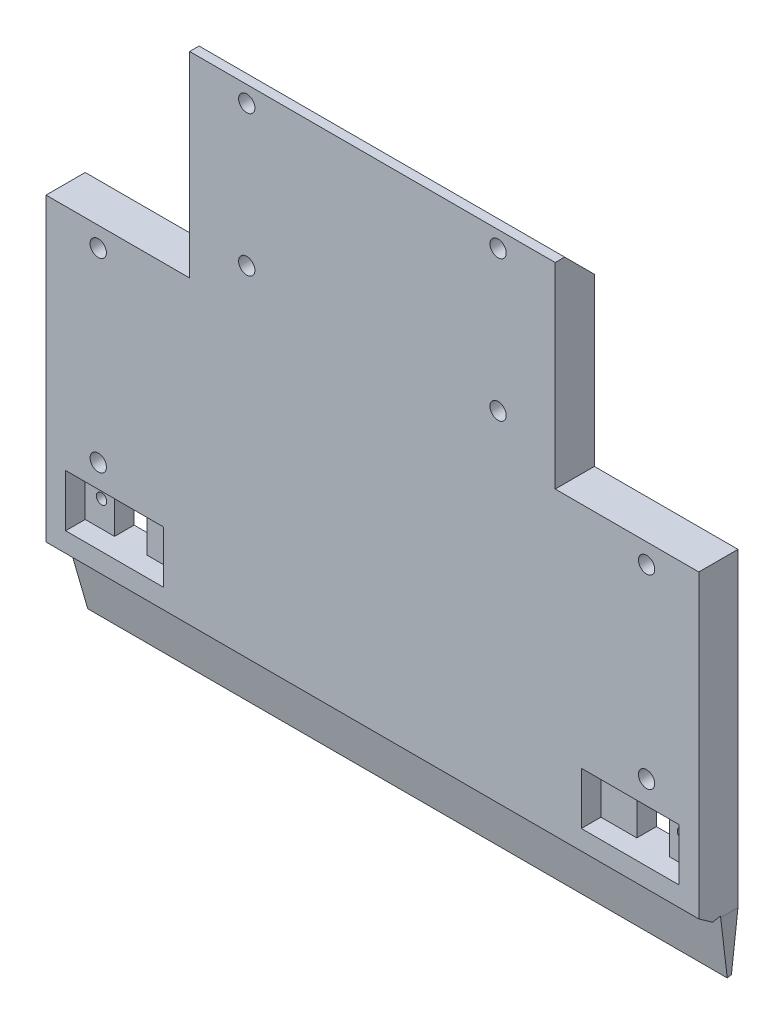
SolidWorks part; units mm, degrees
material "7075-T6, Chapa (SS)"
ref_plane "Plano frontal" through (0, 0, 0) normal (0, 0, 1) x (1, 0, 0)
ref_plane "Plano superior" through (0, 0, 0) normal (0, 1, 0) x (1, 0, 0)
ref_plane "Plano direito" through (0, 0, 0) normal (1, 0, 0) x (0, 0, -1)
sketch "Esboço1" plane through (0, 0, 0) normal (0, 0, 1) x (1, 0, 0)
  line L0 (0, 62) -> (22, 62)
  line L2 (0, 62) -> (0, 0)
  line L3 (0, 0) -> (100, 0)
  line L4 (100, 62) -> (100, 0)
  line L7 (78, 96) -> (22, 96)
  line L17 (22, 62) -> (22, 96)
  line L18 (78, 96) -> (78, 62)
  line L19 (78, 62) -> (100, 62)
  dimension "D1" = 100
  dimension "D2" = 96
  dimension "D3" = 34
  dimension "D4" = 22
  dimension "D5" = 22
  dimension "D6" = 34
  dimension "D7" = 0
  dimension "D8" = 0
extrude "Ressalto-extrusão1" add sketch "Esboço1" along normal blind 6
sketch "Esboço2" plane through (0, 0, 0) normal (-1, 0, 0) x (0, 0, 1)
  line L0 (0, 0) -> (2.7029, 12.7159)
  line L1 (4.346, 12.7159) -> (6, 12.7159)
  line L2 (6, 62) -> (6, 0) construction
  line L3 (6, 12.7159) -> (6, 0)
  line L4 (6, 0) -> (0, 0)
  line L5 (0, 62) -> (0, 0) construction
  line L6 (2.7029, 12.7159) -> (4.2749, 12.3818)
  line L7 (4.2749, 12.3818) -> (4.346, 12.7159)
  dimension "D1" = 12
  dimension "D2" = 13
  dimension "D3" = 90
extrude "Corte-extrusão1" cut sketch "Esboço2" against normal blind 100
sketch "Esboço3" plane through (78, 0, 0) normal (1, 0, 0) x (0, 0, -1)
  line L0 (-6, 91.5) -> (0, 85.5)
  line L1 (-6, 62) -> (-6, 96) construction
  line L2 (0, 62) -> (0, 96) construction
  line L3 (0, 85.5) -> (0, 96)
  line L4 (0, 96) -> (-6, 96)
  line L5 (-6, 96) -> (0, 96) construction
  line L6 (-6, 96) -> (-6, 91.5)
  dimension "D1" = 4.5
  dimension "D2" = 45
extrude "Corte-extrusão2" cut sketch "Esboço3" against normal blind 100
sketch "Esboço4" plane through (100, 0, 0) normal (1, 0, 0) x (0, 0, -1)
  line L0 (-4.2749, 12.3818) -> (-2.7029, 12.7159) construction
  line L1 (-6, 12.7159) -> (-6, 62) construction
  line L2 (-3.8766, 12.4664) -> (-6, 11.8318)
  line L3 (-6, 11.8318) -> (-6, 13.9664)
  line L4 (-6, 13.9664) -> (-3.8766, 12.4664)
  dimension "D1" = 1.2
  dimension "D2" = 1.5
extrude "Corte-extrusão3" cut sketch "Esboço4" against normal blind 100
fillet "Filete1" radius 0.1 1 edges at (50, 0, 0)
sketch "Esboço5" plane through (0, 0, 6) normal (0, 0, 1) x (1, 0, 0)
  line L0 (0, 12.4664) -> (1.3138, 0.1687)
  line L1 (0, 12.4664) -> (100, 12.4664) construction
  line L2 (0, 12.4664) -> (0, 13.9664) construction
  line L3 (1.3138, 0.1687) -> (0, 0.8514)
  line L4 (0, 0.8514) -> (100, 0.8514) construction
  line L5 (0, 0.8514) -> (0, 12.4664)
  line L6 (100, 12.4664) -> (98.6862, 0.1687)
  line L7 (100, 12.7159) -> (100, 0.9306) construction
  line L8 (98.6862, 0.1687) -> (100, 0.8514)
  line L9 (100, 0.8514) -> (100, 12.4664)
extrude "Corte-extrusão4" cut sketch "Esboço5" against normal blind 100
hole_wizard "Broca de rosquear para tarraxa de M31" positions "Esboço7" profile "Esboço8" hole size "M3" standard "ISO" end condition through all
sketch "Esboço7" plane through (0, 0, 6) normal (0, 0, 1) x (1, 0, 0)
  point P0 (92, 56.9664)
  point P2 (92, 28.5209)
  point P4 (8, 56.9664)
  point P6 (8, 28.5209)
sketch "Esboço8" plane through (92, 56.9664, 6) normal (1, 0, 0) x (0, -1, 0)
  line L0 (0, 0) -> (0, 6)
  line L1 (0, 6) -> (1.25, 6)
  line L2 (1.25, 6) -> (1.25, 0)
  line L5 (1.25, 0) -> (0, 0)
  line L11 (0, -6.35) -> (0, 107.95) construction
  dimension "Thru Hole Dia." = 2.5
  dimension "Thru Hole Depth" = 6
sketch "Esboço9" plane through (0, 0, 6) normal (0, 0, 1) x (1, 0, 0)
  line L0 (0, 62) -> (0, 13.9664) construction
  line L1 (3, 16.9664) -> (18, 16.9664)
  line L2 (3, 16.9664) -> (3, 24.9664)
  line L3 (3, 24.9664) -> (18, 24.9664)
  line L4 (18, 16.9664) -> (18, 24.9664)
  line L5 (97, 16.9664) -> (82, 16.9664)
  line L6 (97, 16.9664) -> (97, 24.9664)
  line L7 (97, 24.9664) -> (82, 24.9664)
  line L8 (82, 16.9664) -> (82, 24.9664)
  line L9 (100, 13.9664) -> (100, 62) construction
  line L10 (0, 13.9664) -> (100, 13.9664) construction
  dimension "D1" = 8
  dimension "D2" = 15
  dimension "D3" = 3
  dimension "D4" = 8
  dimension "D5" = 3
  dimension "D6" = 15
  dimension "D7" = 3
  dimension "D8" = 3
extrude "Corte-extrusão5" cut sketch "Esboço9" against normal blind 3
sketch "Esboço10" plane through (0, 0, 0) normal (0, 0, -1) x (-1, 0, 0)
  line L0 (-100, 12.4664) -> (-100, 62) construction
  line L1 (-87.5, 16.9664) -> (-92.5, 16.9664)
  line L2 (-87.5, 16.9664) -> (-87.5, 24.9664)
  line L3 (-87.5, 24.9664) -> (-92.5, 24.9664)
  line L4 (-92.5, 16.9664) -> (-92.5, 24.9664)
  line L5 (-50, 93.4018) -> (-50, -39.1507) construction
  line L6 (-12.5, 16.9664) -> (-7.5, 16.9664)
  line L7 (-7.5, 16.9664) -> (-7.5, 24.9664)
  line L8 (-12.5, 24.9664) -> (-7.5, 24.9664)
  line L9 (-12.5, 16.9664) -> (-12.5, 24.9664)
  line L10 (-3, 24.9664) -> (-3, 16.9664) construction
  dimension "D1" = 5
  dimension "D2" = 8
  dimension "D3" = 7.5
  dimension "D4" = 4.5
extrude "Corte-extrusão6" cut sketch "Esboço10" against normal blind 3
hole_wizard "Broca de rosquear para tarraxa de M21" positions "Esboço11" profile "Esboço12" hole size "M2" standard "ISO" end condition through all
sketch "Esboço11" plane through (0, 0, 3) normal (0, 0, 1) x (1, 0, 0)
  line L1 (82, 16.9664) -> (97, 16.9664) construction
  line L2 (89.5, 16.9664) -> (89.5, 24.9664) construction
  line L3 (97, 24.9664) -> (82, 24.9664) construction
  line L4 (10.5, 16.9664) -> (10.5, 24.9664) construction
  line L5 (3, 16.9664) -> (18, 16.9664) construction
  line L6 (18, 24.9664) -> (3, 24.9664) construction
  circle A0 centre (84.5, 20.9664) radius 0.8262
  circle A1 centre (94.5, 20.9664) radius 0.8262
  circle A2 centre (15.5, 20.9664) radius 0.819
  circle A3 centre (5.5, 20.9664) radius 0.819
  point P18 (94.5, 20.9664)
  point P35 (5.5, 20.9664)
sketch "Esboço12" plane through (5.5, 20.9664, 3) normal (1, 0, 0) x (0, -1, 0)
  line L0 (0, 0) -> (0, 3)
  line L1 (0, 3) -> (0.8, 3)
  line L2 (0.8, 3) -> (0.8, 0)
  line L5 (0.8, 0) -> (0, 0)
  line L11 (0, -6.35) -> (0, 107.95) construction
  dimension "Thru Hole Dia." = 1.6
  dimension "Thru Hole Depth" = 3
hole_wizard "Broca de rosquear para tarraxa de M32" positions "Esboço13" profile "Esboço14" hole size "M3" standard "ISO" end condition through all
sketch "Esboço13" plane through (0, 0, 0) normal (0, 0, -1) x (-1, 0, 0)
  point P0 (-30.75, 66)
  point P4 (-69.25, 66)
  point P6 (-69.25, 87.5515)
  point P10 (-30.75, 87.5515)
sketch "Esboço14" plane through (30.75, 66, 0) normal (1, 0, 0) x (0, 1, 0)
  line L0 (0, 0) -> (0, 6)
  line L1 (0, 6) -> (1.25, 6)
  line L2 (1.25, 6) -> (1.25, 0)
  line L5 (1.25, 0) -> (0, 0)
  line L11 (0, -6.35) -> (0, 107.95) construction
  dimension "Thru Hole Dia." = 2.5
  dimension "Thru Hole Depth" = 6
sketch "Esboço15" plane through (0, 0, 6) normal (0, 0, 1) x (1, 0, 0)
  line L0 (22, 91.5) -> (22, 62) construction
  line L1 (22, 90.0515) -> (78.2659, 90.0515)
  line L2 (22, 90.0515) -> (22, 95.4615)
  line L3 (22, 95.4615) -> (78.2659, 95.4615)
  line L4 (78.2659, 90.0515) -> (78.2659, 95.4615)
extrude "Corte-extrusão7" cut sketch "Esboço15" against normal blind 5
sketch "Esboço16" plane through (0, 0, 0) normal (0, 0, -1) x (-1, 0, 0)
  line L0 (0, 62) -> (0, 12.4664) construction
  line L1 (0, 62) -> (-22, 62)
  line L2 (0, 62) -> (0, 60)
  line L3 (0, 60) -> (-22, 60)
  line L4 (-22, 62) -> (-22, 60)
  line L5 (-22, 62) -> (0, 62) construction
  line L6 (-100, 62) -> (-78, 62) construction
  line L7 (-78, 62) -> (-100, 62)
  line L8 (-78, 62) -> (-78, 60)
  line L9 (-78, 60) -> (-100, 60)
  line L10 (-100, 62) -> (-100, 60)
  line L11 (-100, 12.4664) -> (-100, 62) construction
  dimension "D1" = 22
  dimension "D2" = 2
  dimension "D3" = 2
extrude "Corte-extrusão8" cut sketch "Esboço16" against normal blind 10
sketch "Esboço17" plane through (0, 0, 0) normal (-1, 0, 0) x (0, 0, 1)
  line L0 (0.6237, 2.9344) -> (0, 3.067)
  line L1 (2.6498, 12.4664) -> (0.1978, 0.9306) construction
  line L2 (0, 0.9514) -> (0, 12.4664) construction
  line L3 (0, 3.067) -> (0, 0)
  line L4 (0, 0) -> (0.6237, 2.9344)
  dimension "D1" = 3
extrude "Corte-extrusão9" cut sketch "Esboço17" against normal blind 100
